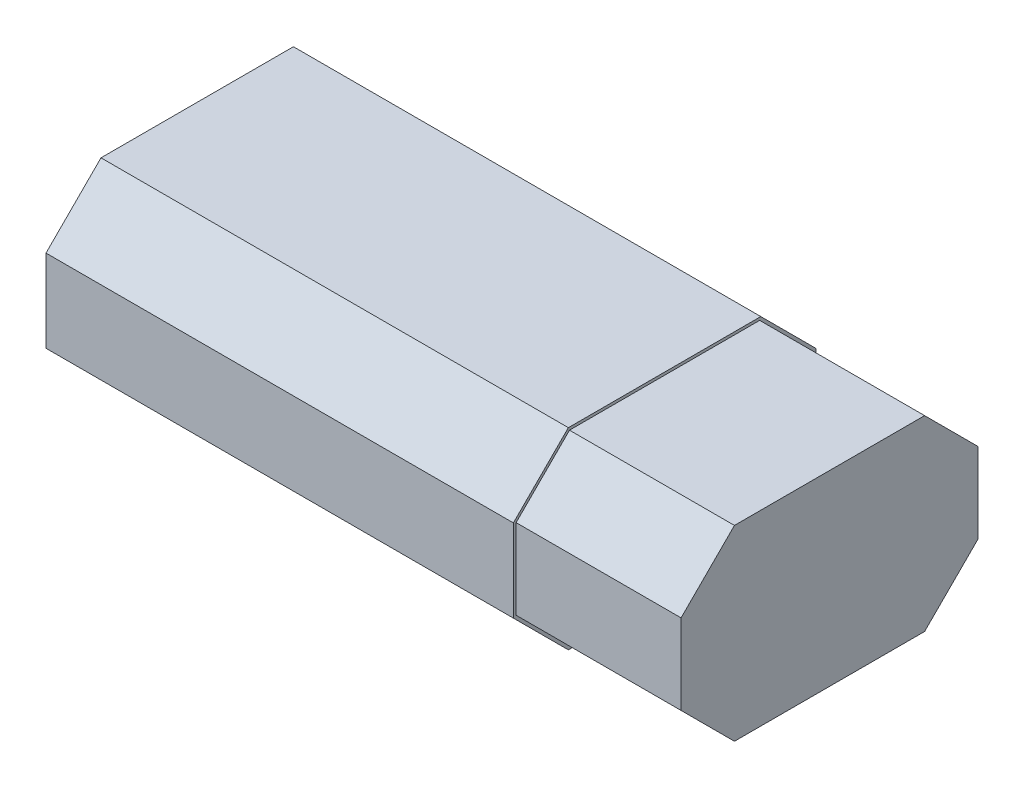
SolidWorks part; units mm, degrees
ref_plane "Front Plane" through (0, 0, 0) normal (0, 0, 1) x (1, 0, 0)
ref_plane "Top Plane" through (0, 0, 0) normal (0, 1, 0) x (1, 0, 0)
ref_plane "Right Plane" through (0, 0, 0) normal (1, 0, 0) x (0, 0, -1)
sketch "Sketch1" plane through (0, 0, 0) normal (1, 0, 0) x (0, 0, -1)
  line L0 (-17.5, 17.5) -> (-27.5, 7.5)
  line L1 (17.5, 17.5) -> (-17.5, 17.5)
  line L2 (27.5, 7.5) -> (27.5, -7.5)
  line L3 (17.5, -17.5) -> (-17.5, -17.5)
  line L4 (-27.5, 7.5) -> (-27.5, -7.5)
  line L5 (27.5, 17.5) -> (-27.5, -17.5) construction
  line L6 (27.5, -17.5) -> (-27.5, 17.5) construction
  line L7 (27.5, 7.5) -> (17.5, 17.5)
  line L8 (27.5, -7.5) -> (17.5, -17.5)
  line L9 (-17.5, -17.5) -> (-27.5, -7.5)
  point P0 (0, 0)
  dimension "D1" = 55
  dimension "D2" = 35
extrude "Boss-Extrude1" add sketch "Sketch1" along normal blind 115
sketch "Sketch2" plane through (115, 0, 0) normal (1, 0, 0) x (0, 0, -1)
  line L36 (27.5, 7.5) -> (17.5, 17.5)
  line L37 (17.5, 17.5) -> (-17.5, 17.5)
  line L38 (-17.5, 17.5) -> (-27.5, 7.5)
  line L39 (-27.5, 7.5) -> (-27.5, -7.5)
  line L40 (-27.5, -7.5) -> (-17.5, -17.5)
  line L41 (-17.5, -17.5) -> (17.5, -17.5)
  line L42 (17.5, -17.5) -> (27.5, -7.5)
  line L43 (27.5, -7.5) -> (27.5, 7.5)
  line L44 (27, 7.2929) -> (17.2929, 17)
  line L45 (27, -7.2929) -> (27, 7.2929)
  line L46 (17.2929, -17) -> (27, -7.2929)
  line L47 (-17.2929, -17) -> (17.2929, -17)
  line L48 (-27, -7.2929) -> (-17.2929, -17)
  line L49 (-27, 7.2929) -> (-27, -7.2929)
  line L50 (-17.2929, 17) -> (-27, 7.2929)
  line L51 (17.2929, 17) -> (-17.2929, 17)
  line L52 (27, 7.2929) -> (17.2929, 17)
  line L53 (27, -7.2929) -> (27, 7.2929)
  line L54 (17.2929, -17) -> (27, -7.2929)
  line L55 (-17.2929, -17) -> (17.2929, -17)
  line L56 (-27, -7.2929) -> (-17.2929, -17)
  line L57 (-27, 7.2929) -> (-27, -7.2929)
  line L58 (-17.2929, 17) -> (-27, 7.2929)
  line L59 (17.2929, 17) -> (-17.2929, 17)
  dimension "D1" = 0.5
  dimension "D2" = 0.5
extrude "Cut-Extrude1" cut sketch "Sketch2" against normal blind 30
